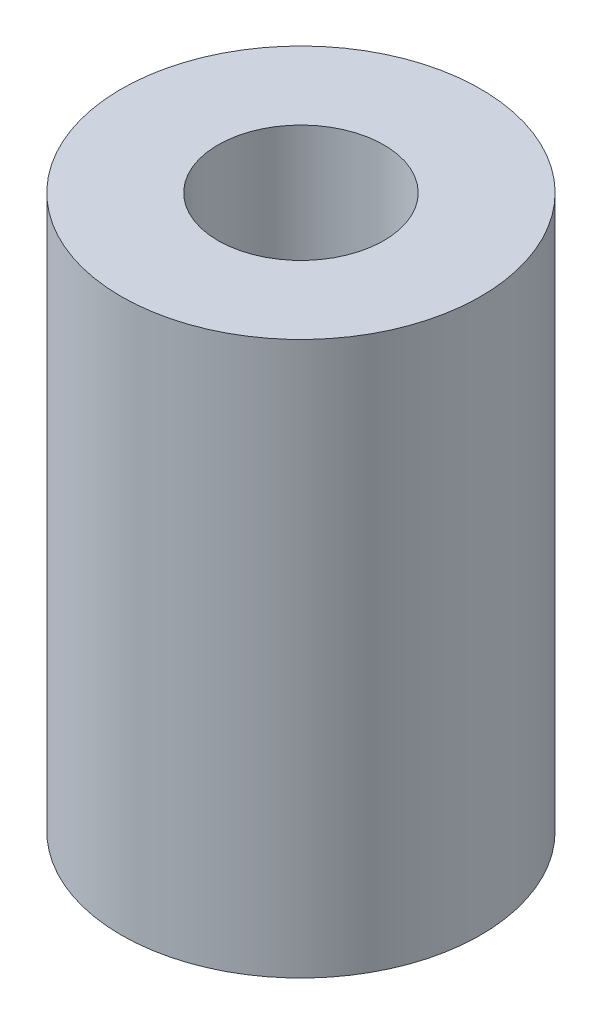
SolidWorks part; units mm, degrees
ref_plane "Plan de face" through (0, 0, 0) normal (0, 0, 1) x (1, 0, 0)
ref_plane "Plan de dessus" through (0, 0, 0) normal (0, 1, 0) x (1, 0, 0)
ref_plane "Plan de droite" through (0, 0, 0) normal (1, 0, 0) x (0, 0, -1)
sketch "Esquisse1" plane through (0, 0, 0) normal (0, 1, 0) x (1, 0, 0)
  circle A0 centre (0, 0) radius 1.5
  dimension "D1" = 3
sketch "Esquisse2" plane through (0, 0, 0) normal (0, 1, 0) x (1, 0, 0)
  circle A0 centre (0, 0) radius 3.25
  dimension "D1" = 6.5
extrude "Boss.-Extru.1" add sketch "Esquisse2" along normal blind 10
extrude "Enlèv. mat.-Extru.1" cut sketch "Esquisse1" along normal blind 28
